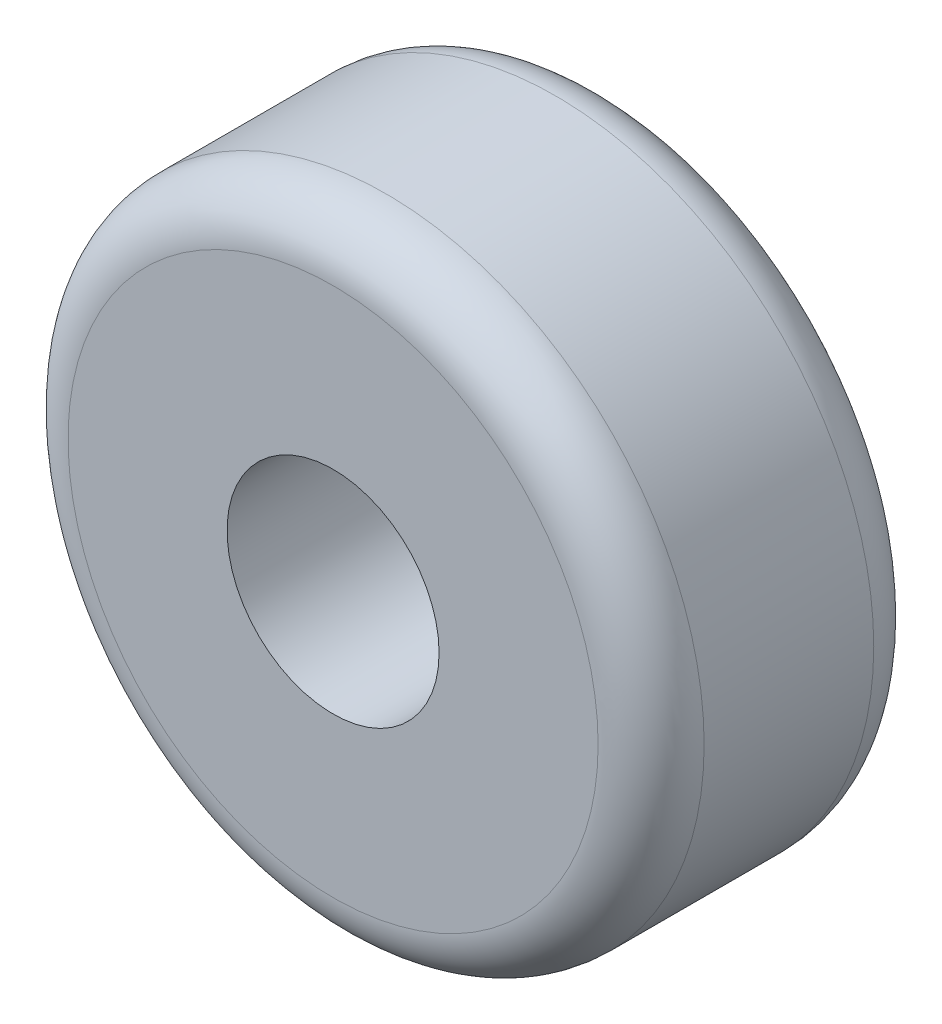
SolidWorks part; units mm, degrees
ref_plane "Plan de face" through (0, 0, 0) normal (0, 0, 1) x (1, 0, 0)
ref_plane "Plan de dessus" through (0, 0, 0) normal (0, 1, 0) x (1, 0, 0)
ref_plane "Plan de droite" through (0, 0, 0) normal (1, 0, 0) x (0, 0, -1)
sketch "Esquisse1" plane through (0, 0, 0) normal (0, 0, 1) x (1, 0, 0)
  circle A0 centre (0, 0) radius 12
  dimension "D1" = 24
extrude "Boss.-Extru.1" add sketch "Esquisse1" along normal blind 10.4
fillet "Congé1" radius 2 1 edges at (12, 0, 10.4)
fillet "Congé2" radius 2 1 edges at (12, 0, 0)
sketch "Esquisse2" plane through (0, 0, 0) normal (0, 0, 1) x (1, 0, 0)
  circle A0 centre (0, 0) radius 4
  dimension "D1" = 8
extrude "Enlèv. mat.-Extru.1" cut sketch "Esquisse2" along normal blind 10.4
